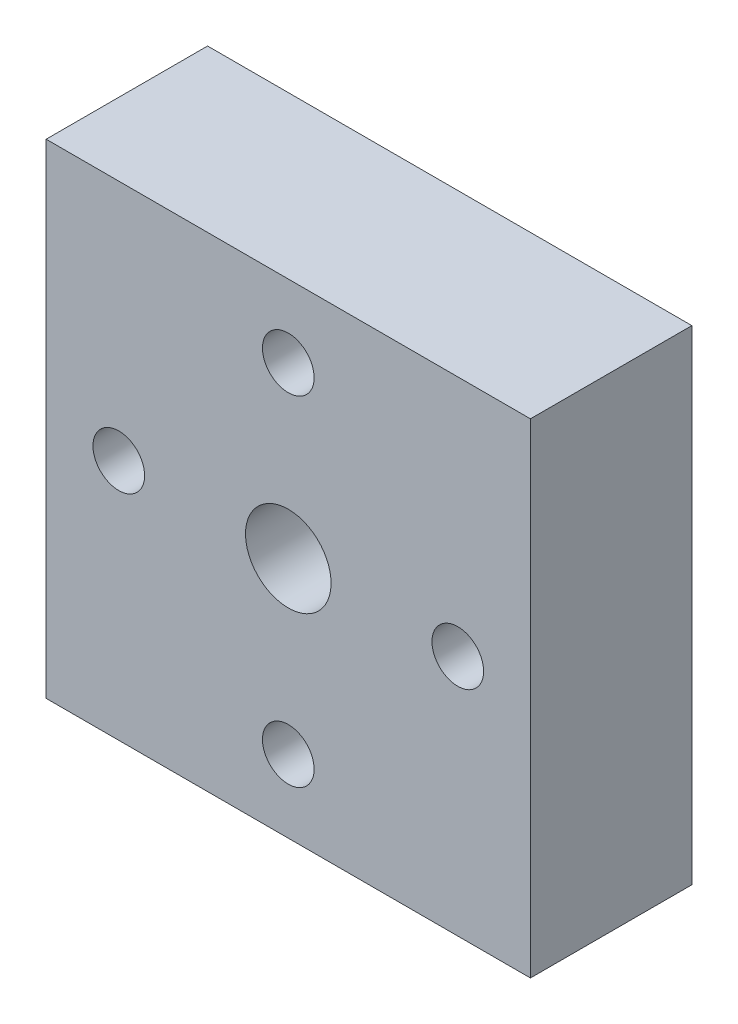
SolidWorks part; units mm, degrees
ref_plane "Front Plane" through (0, 0, 0) normal (0, 0, 1) x (1, 0, 0)
ref_plane "Top Plane" through (0, 0, 0) normal (0, 1, 0) x (1, 0, 0)
ref_plane "Right Plane" through (0, 0, 0) normal (1, 0, 0) x (0, 0, -1)
sketch "Sketch1" plane through (0, 0, 0) normal (1, 0, 0) x (0, 0, -1)
  line L1 (-15, 15) -> (15, 15)
  line L2 (-15, 15) -> (-15, -15)
  line L3 (-15, -15) -> (15, -15)
  line L4 (15, 15) -> (15, -15)
  line L5 (-15, 15) -> (15, -15) construction
  line L6 (-15, -15) -> (15, 15) construction
  point P0 (0, 0)
  dimension "D1" = 30
extrude "Boss-Extrude1" add sketch "Sketch1" along normal blind 30
sketch "Sketch2" plane through (0, 0, -15) normal (0, 0, -1) x (-1, 0, 0)
  line L0 (0, -15) -> (-30, 15) construction
  line L1 (-15, -6.0001) -> (-15, 6.0001) construction
  circle A0 centre (-15, 6.0001) radius 0.65
  circle A1 centre (-21.001, 0.003) radius 0.65
  circle A2 centre (-8.9973, 0.003) radius 0.65
  circle A3 centre (-15, -6.0001) radius 0.65
  point P12 (-15, 0)
  point P13 (-15, 0)
  point P14 (0, 0)
  point P15 (0, 0)
  dimension "D5" = 1.3
  dimension "D1" = 12.0002
  dimension "D3" = 6.0027
  dimension "D4" = 6.0031
extrude "Cut-Extrude1" cut sketch "Sketch2" against normal blind 7
sketch "Sketch3" plane through (0, 0, -15) normal (0, 0, -1) x (-1, 0, 0)
  line L0 (-6.16, -8.84) -> (-23.84, 8.84) construction
  line L1 (-15, 6.0001) -> (-15, -6.0001) construction
  circle A0 centre (-6.16, 8.84) radius 1.95
  circle A1 centre (-23.84, 8.84) radius 1.95
  circle A2 centre (-23.84, -8.84) radius 1.95
  circle A3 centre (-6.16, -8.84) radius 1.95
  point P10 (-15, 0)
  point P11 (-15, 0)
  dimension "D3" = 3.9
  dimension "D1" = 17.68
  dimension "D2" = 17.68
extrude "Boss-Extrude2" add sketch "Sketch3" along normal blind 2
sketch "Sketch4" plane through (0, 0, -15) normal (0, 0, -1) x (-1, 0, 0)
  line L0 (-15, -6.0001) -> (-15, 6.0001) construction
  circle A0 centre (-15, 0) radius 2.5
  circle A1 centre (-15, 0) radius 3.2
  point P7 (-15, 0)
  dimension "D1" = 5
  dimension "D2" = 0.7
extrude "Cut-Extrude2" cut sketch "Sketch4" against normal blind 1
sketch "Sketch5" plane through (0, 0, -15) normal (0, 0, -1) x (-1, 0, 0)
  circle A0 centre (-15, 0) radius 2.65
  dimension "D1" = 5.3
extrude "Cut-Extrude3" cut sketch "Sketch5" against normal through all
sketch "Sketch6" plane through (30, 0, 0) normal (1, 0, 0) x (0, 0, -1)
  line L0 (15, 15) -> (-15, 15) construction
  line L1 (5, 15) -> (-15, 15)
  line L2 (5, 15) -> (5, -17.6663)
  line L3 (5, -17.6663) -> (-15, -17.6663)
  line L4 (-15, 15) -> (-15, -17.6663)
  line L5 (-15, 15) -> (-15, -15) construction
  line L6 (15, -15) -> (15, 15) construction
  dimension "D1" = 10
extrude "Cut-Extrude4" cut sketch "Sketch6" against normal through all
sketch "Sketch7" plane through (0, 0, -15) normal (0, 0, -1) x (-1, 0, 0)
  line L0 (-4.5, 0) -> (-25.5, 0) construction
  line L1 (-15, -10.5) -> (-15, 10.5) construction
  circle A0 centre (-15, 10.5) radius 3
  circle A1 centre (-15, -10.5) radius 3
  circle A2 centre (-25.5, 0) radius 3
  circle A3 centre (-4.5, 0) radius 3
  circle A4 centre (-15, 0) radius 2.65 construction
  point P8 (0, 0)
  point P9 (-4.9849, 0)
  point P10 (-14.3835, -9.0735)
  point P13 (-15, 0)
  point P14 (-15, 0)
  point P15 (-12.9427, -10)
  point P16 (-15.6762, -10)
  point P17 (-15.6692, -10)
  point P18 (0, 0)
  point P19 (-14.13, -10)
  point P20 (-14.673, -10)
  point P21 (0, 0)
  dimension "D1" = 6
  dimension "D2" = 21
  dimension "D3" = 21
extrude "Cut-Extrude5" cut sketch "Sketch7" against normal blind 5
sketch "Sketch8" plane through (0, 0, -10) normal (0, 0, -1) x (-1, 0, 0)
  circle A0 centre (-4.5, 0) radius 1.6
  circle A1 centre (-15, -10.5) radius 1.6
  circle A2 centre (-15, 10.5) radius 1.6
  circle A3 centre (-25.5, 0) radius 1.6
  dimension "D1" = 3.2
extrude "Cut-Extrude6" cut sketch "Sketch8" against normal through all
